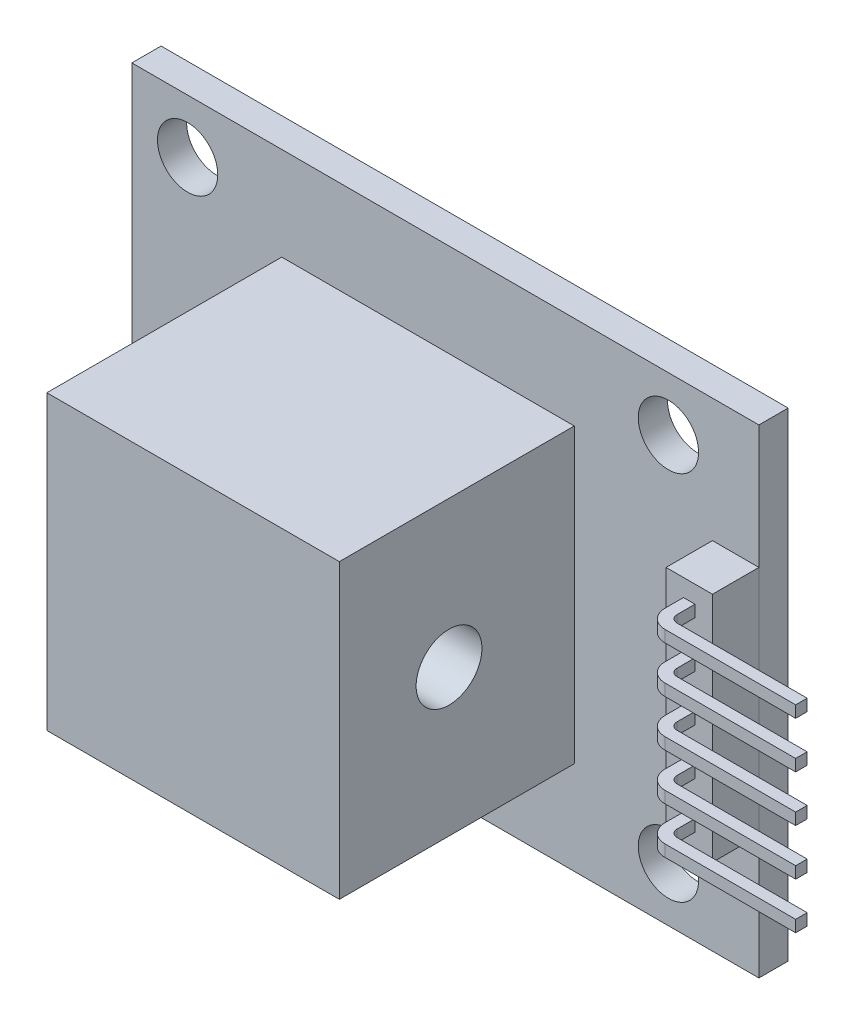
SolidWorks part; units mm, degrees
ref_plane "Front Plane" through (0, 0, 0) normal (0, 0, 1) x (1, 0, 0)
ref_plane "Top Plane" through (0, 0, 0) normal (0, 1, 0) x (1, 0, 0)
ref_plane "Right Plane" through (0, 0, 0) normal (1, 0, 0) x (0, 0, -1)
sketch "Sketch1" plane through (0, 0, 0) normal (0, 0, 1) x (1, 0, 0)
  line L0 (0, 13.1) -> (0, -13.1) construction
  line L1 (-17.15, 13.1) -> (17.15, 13.1)
  line L2 (-17.15, 13.1) -> (-17.15, -13.1)
  line L3 (-17.15, -13.1) -> (17.15, -13.1)
  line L4 (17.15, 13.1) -> (17.15, -13.1)
  line L5 (-17.15, 0) -> (17.15, 0) construction
  line L8 (13.85, 10.15) -> (17.15, 10.15) construction
  line L9 (12.2, 11.8) -> (12.2, 13.1) construction
  circle A0 centre (-14.1, 10.15) radius 1.65
  circle A1 centre (12.2, 10.15) radius 1.65
  circle A2 centre (12.2, -10.15) radius 1.65
  circle A3 centre (-14.1, -10.15) radius 1.65
  dimension "D1" = 3.3
  dimension "D4" = 26.3
  dimension "D2" = 34.3
  dimension "D3" = 26.2
  dimension "D5" = 20.3
  dimension "D8" = 3.3
extrude "PCB" add sketch "Sketch1" along normal blind 1.6
sketch "Sketch2" plane through (0, 0, 1.6) normal (0, 0, 1) x (1, 0, 0)
  line L0 (-14.1, 10.15) -> (-14.1, -10.15) construction
  line L1 (-14.1, -10.15) -> (12.2, -10.15) construction
  line L2 (-0.95, -10.15) -> (-0.95, 10.15) construction
  line L3 (-14.1, 0) -> (12.2, 0) construction
  line L5 (-8.95, -8) -> (7.05, -8)
  line L6 (-8.95, -8) -> (-8.95, 8)
  line L7 (-8.95, 8) -> (7.05, 8)
  line L8 (7.05, -8) -> (7.05, 8)
  line L9 (-8.95, -8) -> (7.05, 8) construction
  line L10 (-8.95, 8) -> (7.05, -8) construction
  point P11 (-0.95, 0)
  dimension "D1" = 16
extrude "Potentiometers" add sketch "Sketch2" along normal blind 12.85 separate body
ref_plane "Potentiometer Plane" through (-0.95, 0, 0) normal (1, 0, 0) x (0, 0, -1)
sketch "Sketch4" plane through (7.05, 0, 0) normal (1, 0, 0) x (0, 0, -1)
  line L0 (-14.45, 0) -> (-1.6, 0) construction
  line L1 (-14.45, -8) -> (-14.45, 8) construction
  line L2 (-1.6, -13.1) -> (-1.6, 13.1) construction
  line L3 (-1.6, -8) -> (-1.6, 8) construction
  circle A0 centre (-8.45, 0) radius 1.8
  dimension "D2" = 3.6
  dimension "D1" = 6.85
extrude "Rotation Axis" cut sketch "Sketch4" against normal through all
sketch "Sketch5" plane through (0, 0, 1.6) normal (0, 0, 1) x (1, 0, 0)
  line L0 (0, 0) -> (17.15, 0) construction
  line L1 (17.15, -13.1) -> (17.15, 13.1) construction
  line L3 (17.15, 6.35) -> (14.61, 6.35)
  line L4 (17.15, 6.35) -> (17.15, -6.35)
  line L5 (17.15, -6.35) -> (14.61, -6.35)
  line L6 (14.61, 6.35) -> (14.61, -6.35)
  dimension "D1" = 12.7
  dimension "D2" = 2.54
extrude "Header Base" add sketch "Sketch5" along normal blind 2.54 separate body
ref_plane "Plane1" through (0, -5.08, 0) normal (0, -1, 0) x (-1, 0, 0)
sketch "Sketch6" plane through (0, -5.08, 0) normal (0, -1, 0) x (-1, 0, 0)
  line L0 (-15.88, -4.14) -> (-15.88, -6.0647) construction
  line L1 (-14.61, -4.14) -> (-17.15, -4.14) construction
  line L2 (-15.565, -4.14) -> (-15.565, -5.155)
  line L3 (-16.565, -6.155) -> (-23.715, -6.155)
  line L4 (-23.715, -6.155) -> (-23.715, -5.525)
  line L5 (-23.715, -5.525) -> (-16.595, -5.525)
  line L6 (-16.195, -5.125) -> (-16.195, -4.14)
  line L7 (-16.195, -4.14) -> (-15.565, -4.14)
  line L8 (-23.715, -5.84) -> (-15.565, -5.84) construction
  arc A0 (-15.565, -5.155) -> (-16.565, -6.155) centre (-16.565, -5.155) cw
  arc A1 (-16.195, -5.125) -> (-16.595, -5.525) centre (-16.595, -5.125) cw
  dimension "D4" = 1
  dimension "D5" = 0.4
  dimension "D1" = 0.63
  dimension "D2" = 0.63
  dimension "D3" = 1.7
  dimension "D6" = 8.15
extrude "Right Angle Pin" add sketch "Sketch6" along normal mid plane 0.64
pattern_linear "LPattern1" count 5 spacing 2.54 along (0, 1, 0) of "Right Angle Pin"
equation "\"D1@Potentiometers\"=14.45-1.6"
equation "\"D1@Plane1\"=2.54mm/2"
